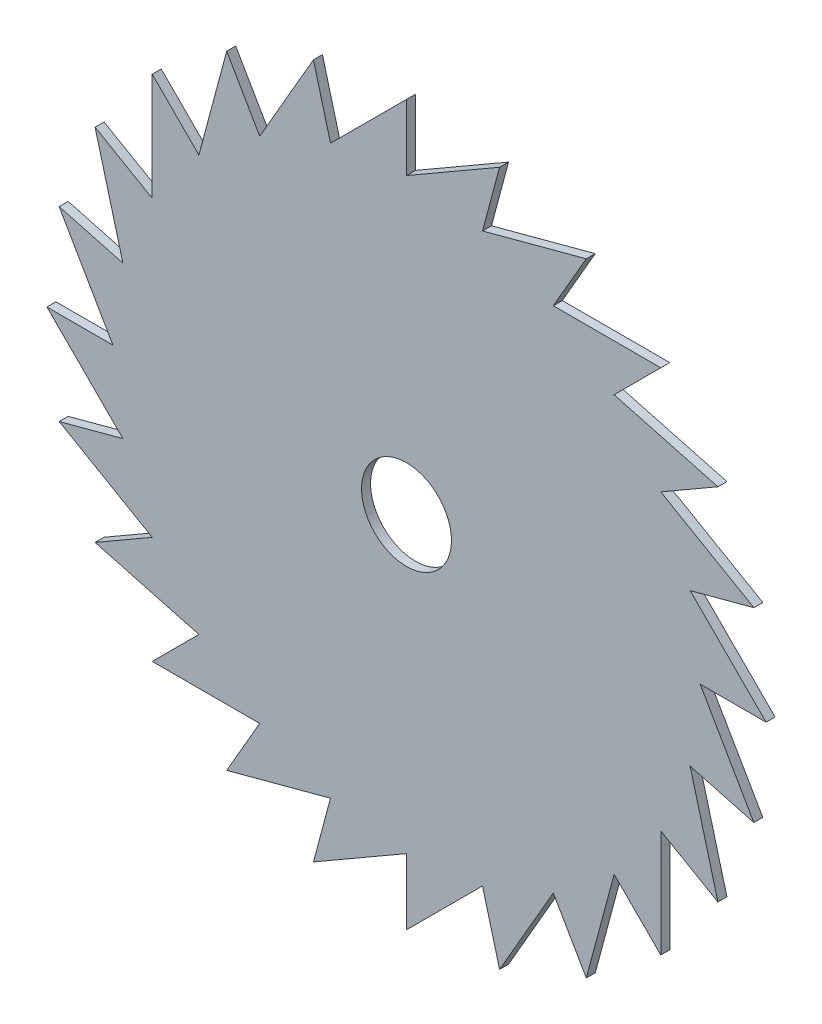
SolidWorks part; units mm, degrees
ref_plane "Front Plane" through (0, 0, 0) normal (0, 0, 1) x (1, 0, 0)
ref_plane "Top Plane" through (0, 0, 0) normal (0, 1, 0) x (1, 0, 0)
ref_plane "Right Plane" through (0, 0, 0) normal (1, 0, 0) x (0, 0, -1)
sketch "Sketch1" plane through (0, 0, 0) normal (0, 0, 1) x (1, 0, 0)
  line L0 (0, 0) -> (5.6741, 21.1759) construction
  line L1 (0, 0) -> (0, 65.3197) construction
  line L2 (0, 40) -> (0, 32.6599)
  line L3 (0, 32.6599) -> (10.3528, 38.637)
  line L4 (8.453, 31.547) -> (20, 34.641)
  line L5 (10.3528, 38.637) -> (8.453, 31.547)
  line L6 (16.3299, 28.2843) -> (28.2843, 28.2843)
  line L7 (20, 34.641) -> (16.3299, 28.2843)
  line L8 (23.094, 23.094) -> (34.641, 20)
  line L9 (28.2843, 28.2843) -> (23.094, 23.094)
  line L10 (28.2843, 16.3299) -> (38.637, 10.3528)
  line L11 (34.641, 20) -> (28.2843, 16.3299)
  line L12 (31.547, 8.453) -> (40, 0)
  line L13 (38.637, 10.3528) -> (31.547, 8.453)
  line L14 (32.6599, 0) -> (38.637, -10.3528)
  line L15 (40, 0) -> (32.6599, 0)
  line L16 (31.547, -8.453) -> (34.641, -20)
  line L17 (38.637, -10.3528) -> (31.547, -8.453)
  line L18 (28.2843, -16.3299) -> (28.2843, -28.2843)
  line L19 (34.641, -20) -> (28.2843, -16.3299)
  line L20 (23.094, -23.094) -> (20, -34.641)
  line L21 (28.2843, -28.2843) -> (23.094, -23.094)
  line L22 (16.3299, -28.2843) -> (10.3528, -38.637)
  line L23 (20, -34.641) -> (16.3299, -28.2843)
  line L24 (8.453, -31.547) -> (0, -40)
  line L25 (10.3528, -38.637) -> (8.453, -31.547)
  line L26 (0, -32.6599) -> (-10.3528, -38.637)
  line L27 (0, -40) -> (0, -32.6599)
  line L28 (-8.453, -31.547) -> (-20, -34.641)
  line L29 (-10.3528, -38.637) -> (-8.453, -31.547)
  line L30 (-16.3299, -28.2843) -> (-28.2843, -28.2843)
  line L31 (-20, -34.641) -> (-16.3299, -28.2843)
  line L32 (-23.094, -23.094) -> (-34.641, -20)
  line L33 (-28.2843, -28.2843) -> (-23.094, -23.094)
  line L34 (-28.2843, -16.3299) -> (-38.637, -10.3528)
  line L35 (-34.641, -20) -> (-28.2843, -16.3299)
  line L36 (-31.547, -8.453) -> (-40, 0)
  line L37 (-38.637, -10.3528) -> (-31.547, -8.453)
  line L38 (-32.6599, 0) -> (-38.637, 10.3528)
  line L39 (-40, 0) -> (-32.6599, 0)
  line L40 (-31.547, 8.453) -> (-34.641, 20)
  line L41 (-38.637, 10.3528) -> (-31.547, 8.453)
  line L42 (-28.2843, 16.3299) -> (-28.2843, 28.2843)
  line L43 (-34.641, 20) -> (-28.2843, 16.3299)
  line L44 (-23.094, 23.094) -> (-20, 34.641)
  line L45 (-28.2843, 28.2843) -> (-23.094, 23.094)
  line L46 (-16.3299, 28.2843) -> (-10.3528, 38.637)
  line L47 (-20, 34.641) -> (-16.3299, 28.2843)
  line L48 (-8.453, 31.547) -> (0, 40)
  line L49 (-10.3528, 38.637) -> (-8.453, 31.547)
  circle A0 centre (0, 0) radius 40 construction
  circle A1 centre (0, 0) radius 5
  point P80 (0, 0)
  dimension "D1" = 80
  dimension "D5" = 10
  dimension "D2" = 15
  dimension "D3" = 60
  dimension "D4" = 24
extrude "Boss-Extrude1" add sketch "Sketch1" along normal blind 1
